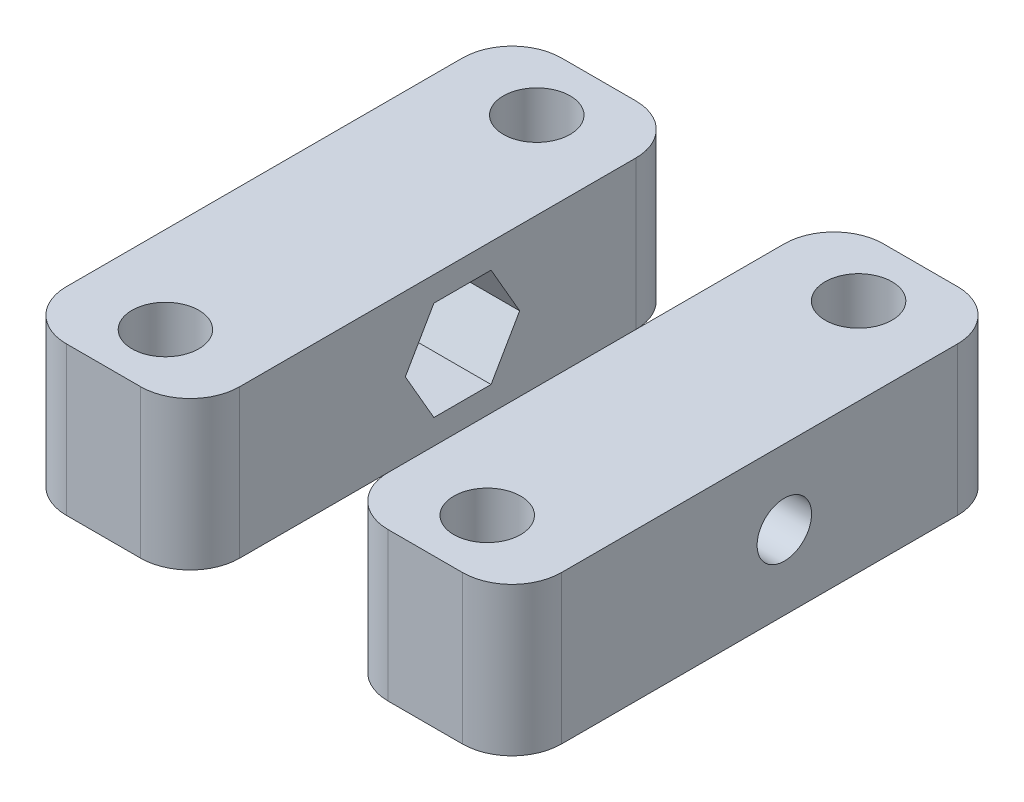
SolidWorks part; units mm, degrees
material "PLA"
ref_plane "前视基准面" through (0, 0, 0) normal (0, 0, 1) x (1, 0, 0)
ref_plane "上视基准面" through (0, 0, 0) normal (0, 1, 0) x (1, 0, 0)
ref_plane "右视基准面" through (0, 0, 0) normal (1, 0, 0) x (0, 0, -1)
sketch "草图1" plane through (0, 0, 0) normal (0, 1, 0) x (1, 0, 0)
  line L1 (-10, -10) -> (10, -10)
  line L2 (-10, -10) -> (-10, 10)
  line L3 (-10, 10) -> (10, 10)
  line L4 (10, -10) -> (10, 10)
  line L5 (0, 10) -> (0, -10) construction
  line L6 (-10, 0) -> (10, 0) construction
  circle A0 centre (-6.5, 7.5) radius 1.35
  circle A1 centre (6.5, 7.5) radius 1.35
  circle A2 centre (6.5, -7.5) radius 1.35
  circle A3 centre (-6.5, -7.5) radius 1.35
  point P0 (0, 0)
  dimension "D5" = 2.7
  dimension "D1" = 15
  dimension "D2" = 13
  dimension "D3" = 20
  dimension "D4" = 20
extrude "凸台-拉伸1" add sketch "草图1" along normal blind 6
sketch "草图2" plane through (0, 6, 0) normal (0, 1, 0) x (1, 0, 0)
  line L0 (-10, -10) -> (10, -10) construction
  line L1 (3, 10) -> (-3, 10)
  line L2 (3, 10) -> (3, -10)
  line L3 (3, -10) -> (-3, -10)
  line L4 (-3, 10) -> (-3, -10)
  line L5 (0, -10) -> (0, 10) construction
  line L6 (3, 0) -> (-3, 0) construction
  line L7 (-10, 10) -> (-10, -10) construction
  point P0 (0, 0)
  dimension "D1" = 7
extrude "切除-拉伸1" cut sketch "草图2" against normal through all
sketch "草图5" plane through (10, 0, 0) normal (1, 0, 0) x (0, 0, -1)
  line L0 (10, 3) -> (-10, 3) construction
  line L1 (10, 6) -> (10, 0) construction
  line L2 (-10, 6) -> (-10, 0) construction
  circle A0 centre (1, 3) radius 1.1
  dimension "D2" = 2.2
  dimension "D1" = 9
extrude "切除-拉伸2" cut sketch "草图5" against normal through all
sketch "草图6" plane through (3, 0, 0) normal (-1, 0, 0) x (0, 0, 1)
  line L1 (0.1547, 5) -> (-2.1547, 5)
  line L2 (-2.1547, 5) -> (-3.3094, 3)
  line L3 (-3.3094, 3) -> (-2.1547, 1)
  line L4 (-2.1547, 1) -> (0.1547, 1)
  line L5 (0.1547, 1) -> (1.3094, 3)
  line L6 (1.3094, 3) -> (0.1547, 5)
  circle A0 centre (-1, 3) radius 2 construction
  dimension "D1" = 4
extrude "切除-拉伸4" cut sketch "草图6" against normal blind 3
sketch "草图7" plane through (-3, 0, 0) normal (1, 0, 0) x (0, 0, -1)
  line L1 (2.1547, 5) -> (-0.1547, 5)
  line L2 (-0.1547, 5) -> (-1.3094, 3)
  line L3 (-1.3094, 3) -> (-0.1547, 1)
  line L4 (-0.1547, 1) -> (2.1547, 1)
  line L5 (2.1547, 1) -> (3.3094, 3)
  line L6 (3.3094, 3) -> (2.1547, 5)
  circle A0 centre (1, 3) radius 2 construction
  dimension "D1" = 4
extrude "切除-拉伸5" cut sketch "草图7" against normal blind 3
fillet "圆角1" radius 2 4 edges at (10, 3, 10) (10, 3, -10) (3, 3, -10) (3, 3, 10)
fillet "圆角2" radius 2 4 edges at (-10, 3, -10) (-3, 3, -10) (-3, 3, 10) (-10, 3, 10)
move or copy body "实体-移动/复制1" [suppressed] bodies to move or copy 112 114
